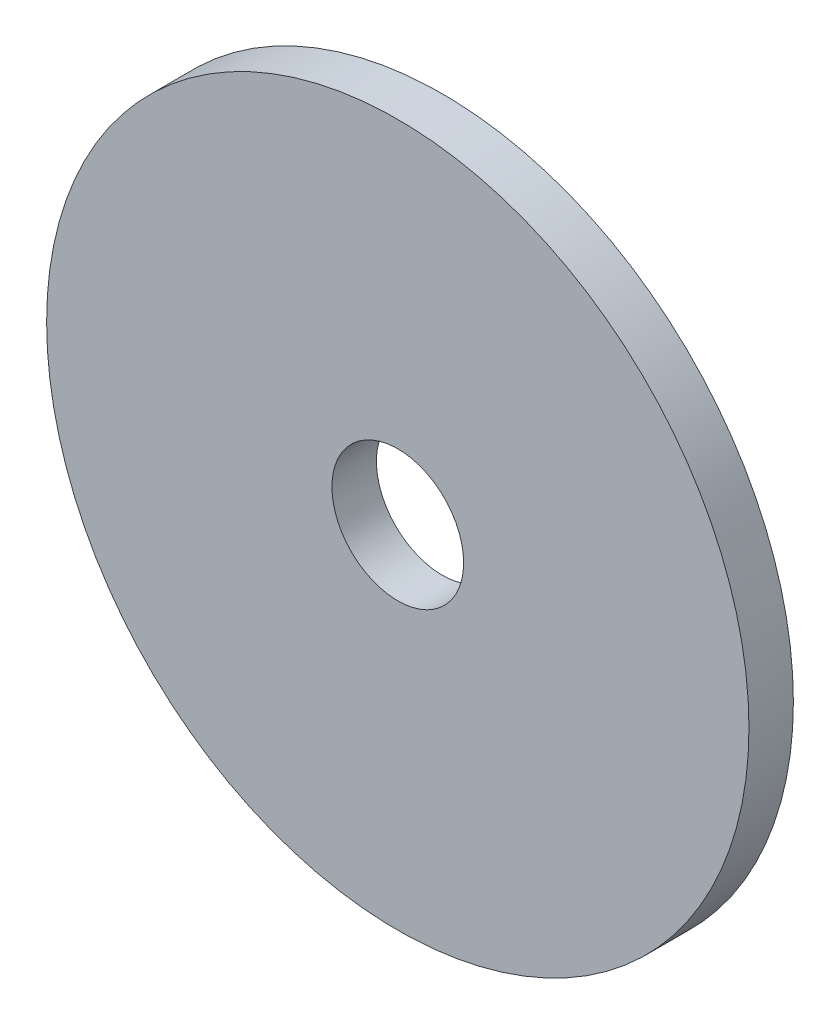
SolidWorks part; units mm, degrees
ref_plane "Alzado" through (0, 0, 0) normal (0, 0, 1) x (1, 0, 0)
ref_plane "Planta" through (0, 0, 0) normal (0, 1, 0) x (1, 0, 0)
ref_plane "Vista lateral" through (0, 0, 0) normal (1, 0, 0) x (0, 0, -1)
sketch "Croquis1" plane through (0, 0, 0) normal (0, 0, 1) x (1, 0, 0)
  line L0 (1.25, 0) -> (-1.25, 0) construction
  circle A0 centre (0, 0) radius 2
  circle A3 centre (0, 0) radius 0.375
  point P7 (0, 0)
  dimension "D1" = 4
  dimension "D2" = 0.75
  dimension "D3" = 2.5
extrude "Saliente-Extruir1" add sketch "Croquis1" along normal blind 0.253
